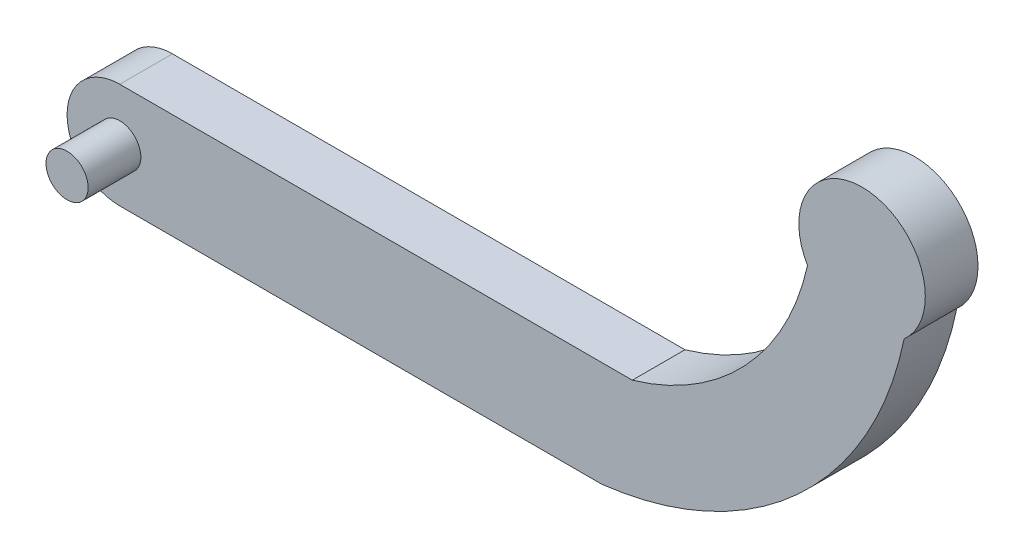
SolidWorks part; units mm, degrees
ref_plane "Alzado" through (0, 0, 0) normal (0, 0, 1) x (1, 0, 0)
ref_plane "Planta" through (0, 0, 0) normal (0, 1, 0) x (1, 0, 0)
ref_plane "Vista lateral" through (0, 0, 0) normal (1, 0, 0) x (0, 0, -1)
sketch "Croquis1" plane through (0, 0, 0) normal (0, 0, 1) x (1, 0, 0)
  line L0 (5.7883, -6.7404) -> (-39.9369, -6.7404)
  line L1 (8.6949, 3.2596) -> (-39.9369, 3.2596)
  arc A0 (-39.9369, -6.7404) -> (-39.9369, 3.2596) centre (-39.9369, -1.7404) cw
  arc A1 (25.3199, 20.9961) -> (8.6949, 3.2596) centre (2.0337, 26.1633) cw
  arc A2 (25.3199, 20.9961) -> (34.4825, 19.5431) centre (30.4973, 24.0285) cw
  arc A3 (34.4825, 19.5431) -> (5.7883, -6.7404) centre (2.0337, 26.1633) cw
extrude "Saliente-Extruir1" add sketch "Croquis1" along normal blind 5
sketch "Croquis2" plane through (0, 0, 0) normal (0, 0, -1) x (-1, 0, 0)
  circle A0 centre (39.9369, -1.7404) radius 2
  dimension "D2" = 4
extrude "Saliente-Extruir2" add sketch "Croquis2" against normal blind 10 contours A0
